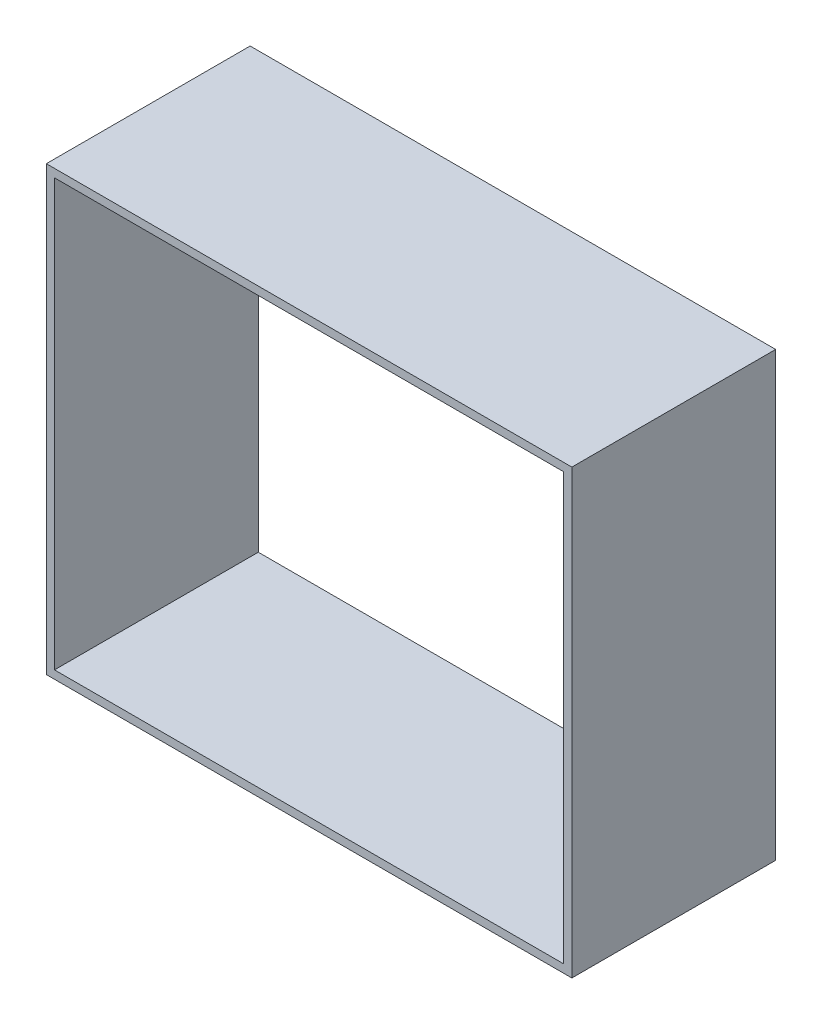
SolidWorks part; units mm, degrees
ref_plane "Front Plane" through (0, 0, 0) normal (0, 0, 1) x (1, 0, 0)
ref_plane "Top Plane" through (0, 0, 0) normal (0, 1, 0) x (1, 0, 0)
ref_plane "Right Plane" through (0, 0, 0) normal (1, 0, 0) x (0, 0, -1)
sketch "Sketch1" plane through (0, 0, 0) normal (0, 0, 1) x (1, 0, 0)
  line L0 (-64.4613, 54.2738) -> (-64.4613, -54.2738)
  line L1 (-62.4613, 52.2738) -> (62.4613, 52.2738)
  line L2 (-62.4613, 52.2738) -> (-62.4613, -52.2738)
  line L3 (-62.4613, -52.2738) -> (62.4613, -52.2738)
  line L4 (62.4613, 52.2738) -> (62.4613, -52.2738)
  line L5 (-62.4613, 52.2738) -> (62.4613, -52.2738) construction
  line L6 (-62.4613, -52.2738) -> (62.4613, 52.2738) construction
  line L7 (-64.4613, -54.2738) -> (64.4613, -54.2738)
  line L8 (64.4613, 54.2738) -> (64.4613, -54.2738)
  line L9 (-64.4613, 54.2738) -> (64.4613, 54.2738)
  point P0 (0, 0)
  dimension "D1" = 2
extrude "Boss-Extrude1" add sketch "Sketch1" along normal blind 50
sketch "Sketch2" plane through (0, 0, 0) normal (0, 0, 1) x (1, 0, 0)
  circle A0 centre (0, 0) radius 48.4966
extrude "Boss-Extrude2" add sketch "Sketch2" along normal up to surface (50 mm away) separate body up to face at (0, 0, 50)
sketch "Sketch3" plane through (0, 0, 0) normal (0, 0, 1) x (1, 0, 0)
  circle A0 centre (-51.1264, 41.5168) radius 6.9941
  circle A1 centre (46.4615, 43.756) radius 6.1207
extrude "Boss-Extrude3" add sketch "Sketch3" along normal blind 20 separate body
delete or keep bodies "Body-Delete1" type delete bodies bodies 103 102 104
